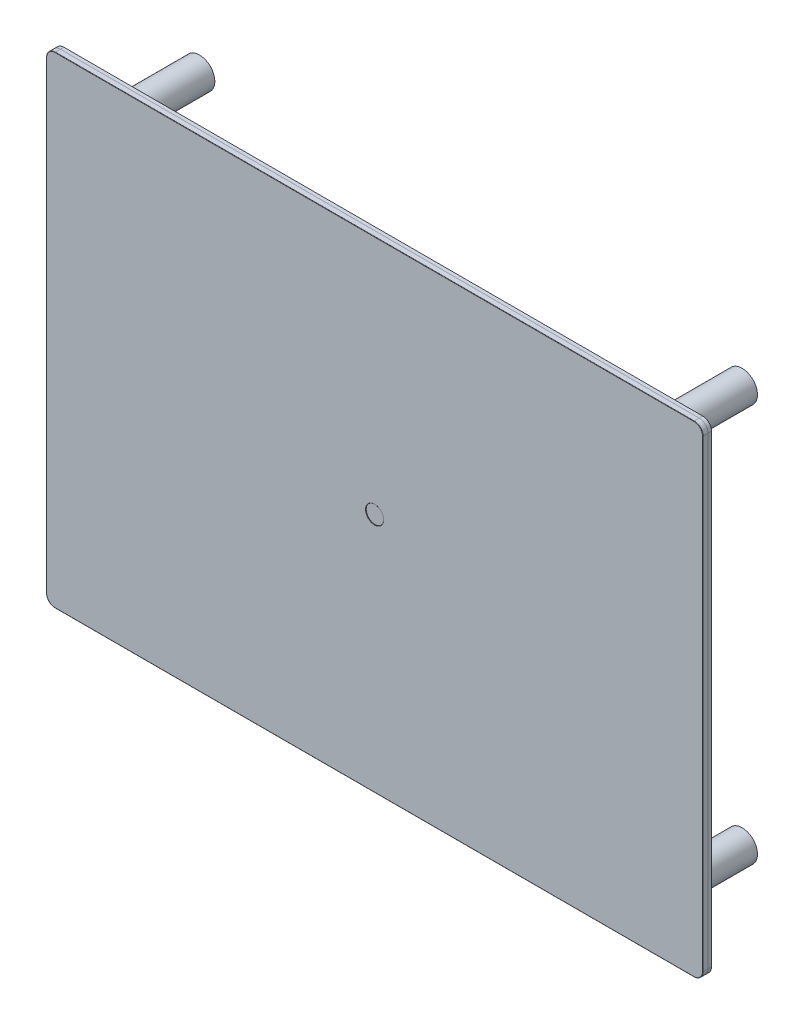
SolidWorks part; units mm, degrees
ref_plane "Ön Düzlem" through (0, 0, 0) normal (0, 0, 1) x (1, 0, 0)
ref_plane "Üst Düzlem" through (0, 0, 0) normal (0, 1, 0) x (1, 0, 0)
ref_plane "Sağ Düzlem" through (0, 0, 0) normal (1, 0, 0) x (0, 0, -1)
sketch "Sketch1" plane through (0, 0, 0) normal (0, 0, 1) x (1, 0, 0)
  line L1 (375, 275) -> (-375, 275)
  line L2 (375, 275) -> (375, -275)
  line L3 (375, -275) -> (-375, -275)
  line L4 (-375, 275) -> (-375, -275)
  line L5 (375, 275) -> (-375, -275) construction
  line L6 (375, -275) -> (-375, 275) construction
  point P0 (0, 0)
  dimension "D1" = 550
  dimension "D2" = 750
extrude "Boss-Extrude1" add sketch "Sketch1" along normal blind 4
sketch "Sketch2" plane through (0, 0, 0) normal (0, 0, -1) x (-1, 0, 0)
  line L1 (0, 0) -> (375, 0) construction
  line L2 (375, 275) -> (375, -275) construction
  line L3 (375, 275) -> (0, 0) construction
  circle A0 centre (310, 227.3333) radius 17.5
  dimension "D1" = 35
  dimension "D2" = 65
extrude "Boss-Extrude2" add sketch "Sketch2" along normal blind 100
mirror "Mirror1" about plane through (0, 0, 0) normal (0, 1, 0) of "Boss-Extrude2"
mirror "Mirror2" about plane through (0, 0, 0) normal (1, 0, 0) of "Mirror1", "Boss-Extrude2"
ref_plane "Plane1" through (0, 0, -30) normal (0, 0, -1) x (-1, 0, 0)
sketch "Sketch3" plane through (0, 0, -30) normal (0, 0, -1) x (-1, 0, 0)
  line L0 (-310, 227.3333) -> (310, 227.3333) construction
  line L1 (0, 0) -> (-312.5, 0) construction
  line L2 (300, 229.8333) -> (-300, 229.8333)
  line L3 (300, 229.8333) -> (300, 224.8333)
  line L4 (300, 224.8333) -> (-300, 224.8333)
  line L5 (-300, 229.8333) -> (-300, 224.8333)
  line L6 (300, 229.8333) -> (-300, 224.8333) construction
  line L7 (300, 224.8333) -> (-300, 229.8333) construction
  line L8 (-307.5, 215) -> (-312.5, 215)
  line L9 (-307.5, 215) -> (-307.5, -215)
  line L10 (-307.5, -215) -> (-312.5, -215)
  line L11 (-312.5, 215) -> (-312.5, -215)
  line L12 (-307.5, 215) -> (-312.5, -215) construction
  line L13 (-307.5, -215) -> (-312.5, 215) construction
  line L14 (0, 227.3333) -> (0, 0) construction
  line L15 (-375, -275) -> (-375, 275) construction
  line L16 (-375, 275) -> (375, 275) construction
  point P4 (0, 227.3333)
  point P9 (-310, 0)
  dimension "D1" = 5
  dimension "D2" = 75
  dimension "D3" = 60
extrude "Boss-Extrude3" add sketch "Sketch3" along normal mid plane 15 separate body
sketch "Sketch4" plane through (312.5, 0, 0) normal (1, 0, 0) x (0, 0, -1)
  line L1 (37.5, -215) -> (22.5, -215) construction
  line L2 (31.75, 215) -> (35.25, 215)
  line L3 (31.75, 215) -> (31.75, -215)
  line L4 (31.75, -215) -> (35.25, -215)
  line L5 (35.25, 215) -> (35.25, -215)
  line L6 (31.75, 215) -> (35.25, -215) construction
  line L7 (31.75, -215) -> (35.25, 215) construction
  line L10 (28.25, 215) -> (24.75, 215)
  line L11 (28.25, 215) -> (28.25, -215)
  line L12 (28.25, -215) -> (24.75, -215)
  line L13 (24.75, 215) -> (24.75, -215)
  line L14 (28.25, 215) -> (24.75, -215) construction
  line L15 (28.25, -215) -> (24.75, 215) construction
  line L16 (30, -215) -> (30, 215) construction
  line L17 (37.5, 215) -> (22.5, 215) construction
  point P0 (33.5, 0)
  point P5 (26.5, 0)
  dimension "D1" = 3.5
  dimension "D2" = 7
extrude "Cut-Extrude1" cut sketch "Sketch4" against normal blind 2
sketch "Sketch5" plane through (0, 229.8333, 0) normal (0, 1, 0) x (1, 0, 0)
  line L0 (27.3843, 22.5) -> (27.3843, 37.5) construction
  line L1 (-300, 35.25) -> (300, 35.25)
  line L2 (-300, 35.25) -> (-300, 31.75)
  line L3 (-300, 31.75) -> (300, 31.75)
  line L4 (300, 35.25) -> (300, 31.75)
  line L5 (-300, 35.25) -> (300, 31.75) construction
  line L6 (-300, 31.75) -> (300, 35.25) construction
  line L7 (-300, 28.25) -> (300, 28.25)
  line L8 (-300, 28.25) -> (-300, 24.75)
  line L9 (-300, 24.75) -> (300, 24.75)
  line L10 (300, 28.25) -> (300, 24.75)
  line L11 (-300, 28.25) -> (300, 24.75) construction
  line L12 (-300, 24.75) -> (300, 28.25) construction
  line L13 (-300, 22.5) -> (300, 22.5) construction
  line L14 (-300, 37.5) -> (300, 37.5) construction
  line L15 (27.3843, 30) -> (-22.9008, 30) construction
  line L16 (-22.9008, 30) -> (-22.9008, 37.5) construction
  line L17 (300, 37.5) -> (300, 22.5) construction
  line L18 (-300, 37.5) -> (-300, 22.5) construction
  point P0 (0, 33.5)
  point P5 (0, 26.5)
  dimension "D1" = 7
  dimension "D2" = 3.5
extrude "Cut-Extrude2" cut sketch "Sketch5" against normal blind 2
mirror "Mirror4" about plane through (0, 0, 0) normal (0, 1, 0) of bodies 108
mirror "Mirror5" about plane through (0, 0, 0) normal (1, 0, 0) of bodies 107
sketch "Sketch7" plane through (0, 0, 4) normal (0, 0, 1) x (1, 0, 0)
  line L4 (-375, 275) -> (-375, -275)
  line L5 (-375, -275) -> (375, -275)
  line L6 (375, -275) -> (375, 275)
  line L7 (375, 275) -> (-375, 275)
  line L8 (-375, 275) -> (-375, -275)
  line L9 (-375, -275) -> (375, -275)
  line L10 (375, -275) -> (375, 275)
  line L11 (375, 275) -> (-375, 275)
  dimension "D1" = 0
extrude "Boss-Extrude4" add sketch "Sketch7" along normal blind 6 separate body
sketch "Sketch8" plane through (0, 0, 10) normal (0, 0, 1) x (1, 0, 0)
  circle A0 centre (0, 0) radius 10
  dimension "D1" = 20
extrude "Cut-Extrude4" cut sketch "Sketch8" against normal blind 0.5
fillet "Fillet1" radius 10 4 edges at (-375, 275, 7) (-375, -275, 7) (375, -275, 7) (375, 275, 7)
fillet "Fillet2" radius 10 4 edges at (375, -275, 2) (375, 275, 2) (-375, -275, 2) (-375, 275, 2)
fillet "Fillet3" radius 0.4 9 edges at (372.0711, 272.0711, 10) (375, 0, 10) (372.0711, -272.0711, 10) (0, -275, 10) (-372.0711, -272.0711, 10) (-375, 0, 10) (-372.0711, 272.0711, 10) (0, 275, 10) (10, 0, 10)
